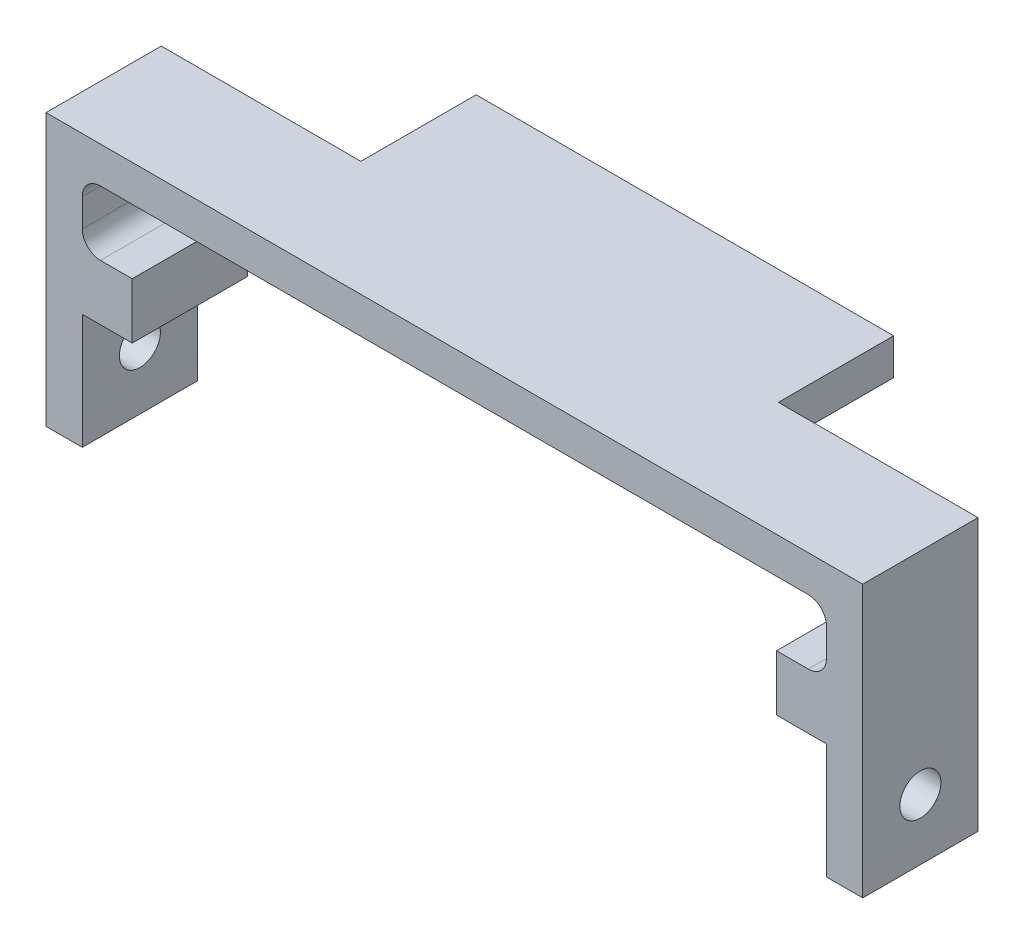
SolidWorks part; units mm, degrees
material "Copper"
ref_plane "Front Plane" through (0, 0, 0) normal (0, 0, 1) x (1, 0, 0)
ref_plane "Top Plane" through (0, 0, 0) normal (0, 1, 0) x (1, 0, 0)
ref_plane "Right Plane" through (0, 0, 0) normal (1, 0, 0) x (0, 0, -1)
sketch "Sketch2" plane through (0, 0, 0) normal (0, 0, 1) x (1, 0, 0)
  line L0 (-1, -12.4725) -> (-1, -6.1225)
  line L1 (-1, -3.0525) -> (-1, -6.1225)
  line L2 (-3, 2.5) -> (42, 2.5)
  line L3 (-1, -6.1225) -> (1.75, -6.1225)
  line L4 (1.75, -6.1225) -> (1.75, -3.0525)
  line L5 (1.75, -3.0525) -> (-1, -3.0525)
  line L6 (-1, -3.0525) -> (-1, 0.5)
  line L7 (-1, 0.5) -> (40, 0.5)
  line L8 (40, 0.5) -> (40, -3.0525)
  line L9 (40, -3.0525) -> (37.25, -3.0525)
  line L10 (37.25, -3.0525) -> (37.25, -6.1225)
  line L11 (37.25, -6.1225) -> (40, -6.1225)
  line L12 (40, -6.1225) -> (40, -12.4725)
  line L13 (40, -12.4725) -> (-1, -12.4725)
  line L14 (-3, 2.5) -> (-3, -12.4725)
  line L15 (-3, -12.4725) -> (42, -12.4725)
  line L16 (0, -8.175) -> (0, -6.175) construction
  line L17 (42, 2.5) -> (42, -12.4725)
  line L18 (0, -6.175) -> (2, -6.175) construction
  line L19 (2, -6.175) -> (2, -3) construction
  line L20 (2, -3) -> (0, -3) construction
  line L21 (0, -3) -> (0, 0) construction
  line L22 (0, 0) -> (39, 0) construction
  line L23 (39, 0) -> (39, -3) construction
  line L24 (39, -3) -> (37, -3) construction
  line L25 (37, -3) -> (37, -6.175) construction
  line L26 (37, -6.175) -> (39, -6.175) construction
  line L27 (39, -6.175) -> (39, -8.175) construction
  line L28 (40, -3.0525) -> (40, -6.1225)
  line L29 (39, -8.175) -> (0, -8.175) construction
  point P27 (1.75, -4.5875)
  point P29 (2, -4.5875)
  point P31 (37, -4.5875)
  point P33 (37.25, -4.5875)
  dimension "D1" = 0.5
  dimension "D6" = 1
  dimension "D11" = 2
  dimension "D13" = 3
  dimension "D14" = 2
  dimension "D15" = 3.175
  dimension "D2" = 1
  dimension "D16" = 2
  dimension "D17" = 2
  dimension "D18" = 2
  dimension "D3" = 3.07
  dimension "D4" = 0.5
  dimension "D5" = 0.5
  dimension "D7" = 6.35
  dimension "D8" = 35
extrude "Boss-Extrude2" add sketch "Sketch2" along normal blind 6.35 contours L17 L2 L14 L15 L0 L3 L4 L5 L6 L7 L8 L9 L10 L11 L12 | L4 L5 L1 L3 | L28 L9 L10 L11
sketch "Sketch3" plane through (0, 2.5, 0) normal (0, 1, 0) x (1, 0, 0)
  line L0 (42, -6.35) -> (42, 0) construction
  line L1 (-3, 0) -> (42, 0)
  line L2 (-3, 0) -> (-3, 6.35)
  line L3 (-3, 6.35) -> (42, 6.35)
  line L4 (42, 0) -> (42, 6.35)
  line L5 (31, 6.35) -> (31, 0)
  line L6 (8, 6.35) -> (8, 0)
  dimension "D1" = 6.35
  dimension "D2" = 11
  dimension "D3" = 11
extrude "Boss-Extrude3" add sketch "Sketch3" against normal up to surface (2 mm away) contours L3 L6 L1 L5 up to face at (19.5, 0.5, 3.175)
hole_wizard "#4-40 Tapped Hole1" positions "3DSketch1" profile "Sketch4" tap size "#4-40" standard "ANSI Inch"
sketch3d "3DSketch1"
  line L6 (1.75, -6.1225, 6.35) -> (-3, -6.1225, 6.35) construction
  line L7 (-3, 2.5, 6.35) -> (-3, -12.4725, 6.35) construction
  line L8 (-3, -6.1225, 6.35) -> (-3, -6.1225, 0) construction
  line L10 (-3, 2.5, 0) -> (-3, -12.4725, 0) construction
  line L12 (-3, -9.1225, 3.175) -> (-3, -6.1225, 3.175) construction
  point P0 (-3, -9.1225, 3.175)
  point P37 (-3, -6.1225, 3.175)
  point P38 (42, -9.1225, 3.175)
  dimension "D1" = 3
cosmetic thread "Hole Thread1" parameters "D1"=2, "D2"=2.8448
sketch "Sketch4" plane through (-3, -9.1225, 3.175) normal (0, 1, 0) x (0, 0, 1)
  line L0 (0, 0) -> (0, 4.5892)
  line L1 (0, 4.5892) -> (1.1303, 3.91)
  line L2 (1.1303, 3.91) -> (1.1303, 0)
  line L5 (1.1303, 0) -> (0, 0)
  line L10 (0, 4.5892) -> (-1.1303, 3.91) construction
  line L11 (0, -6.35) -> (0, 107.95) construction
  dimension "Tap Drill Dia." = 2.2606
  dimension "Tap Drill Depth" = 3.91
  dimension "Drill Angle" = 118
cosmetic thread "Hole Thread2" parameters "D1"=2, "D2"=2.8448
fillet "Fillet1" radius 1 4 edges at (40, 0.5, 3.175) (-1, 0.5, 3.175) (-1, -3.0525, 3.175) (40, -3.0525, 3.175)
equation "\"D6@Sketch2\"=\"D2@Sketch2\""
equation "\"D17@Sketch2\"=\"D16@Sketch2\""
equation "\"D18@Sketch2\"=\"D17@Sketch2\""
equation "\"D5@Sketch2\"=\"D4@Sketch2\""
